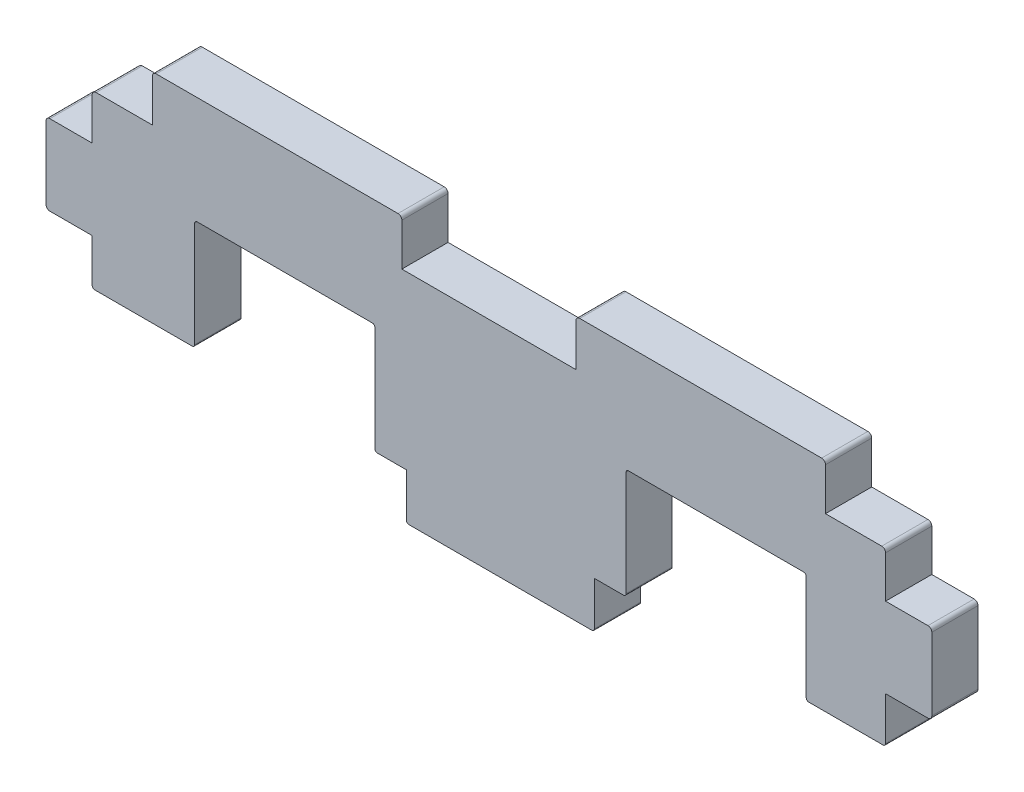
SolidWorks part; units mm, degrees
material "Acrylic (Medium-high impact)"
ref_plane "Front Plane" through (0, 0, 0) normal (0, 0, 1) x (1, 0, 0)
ref_plane "Top Plane" through (0, 0, 0) normal (0, 1, 0) x (1, 0, 0)
ref_plane "Right Plane" through (0, 0, 0) normal (1, 0, 0) x (0, 0, -1)
sketch "Sketch2" plane through (0, 0, 0) normal (0, 0, 1) x (1, 0, 0)
  line L0 (53.6522, 7.7906) -> (53.6522, 4.9881)
  line L2 (-0.8478, 8.0406) -> (-0.8478, 12.7406)
  line L3 (6.3022, 18.9593) -> (22.0022, 18.9593)
  line L4 (56.6522, 8.0406) -> (56.6522, 12.7406)
  line L5 (48.5022, 4.9881) -> (48.5022, 11.8056)
  line L6 (48.3359, 11.9718) -> (36.9684, 11.9718)
  line L7 (36.8022, 4.9881) -> (36.8022, 11.8056)
  line L8 (48.5022, 3.4718) -> (36.8022, 11.9718) construction
  line L9 (48.5022, 11.9718) -> (36.8022, 3.4718) construction
  line L10 (33.8022, 18.9593) -> (49.5022, 18.9593)
  line L11 (2.4022, 15.9593) -> (6.0522, 15.9593)
  line L12 (2.1522, 12.9906) -> (2.1522, 15.7093)
  line L14 (20.5022, 4.9881) -> (20.5022, 11.8056)
  line L15 (20.3359, 11.9718) -> (8.9684, 11.9718)
  line L16 (8.8022, 4.9881) -> (8.8022, 11.8056)
  line L17 (20.5022, 3.4718) -> (8.8022, 11.9718) construction
  line L18 (20.5022, 11.9718) -> (8.8022, 3.4718) construction
  line L19 (53.4859, 4.8218) -> (48.6684, 4.8218)
  line L20 (36.6359, 4.8218) -> (34.7522, 4.8218)
  line L21 (49.7522, 15.9593) -> (53.4022, 15.9593)
  line L22 (6.0522, 15.9593) -> (6.0522, 18.7093)
  line L23 (34.7522, 4.8218) -> (34.7522, 1.9881)
  line L24 (22.2522, 15.9593) -> (22.2522, 18.7093)
  line L25 (34.5859, 1.8218) -> (22.7184, 1.8218)
  line L26 (33.5522, 18.7093) -> (33.5522, 15.9593)
  line L27 (-0.5978, 12.9906) -> (2.1522, 12.9906)
  line L28 (49.7522, 18.7093) -> (49.7522, 15.9593)
  line L29 (22.2522, 15.9593) -> (33.5522, 15.9593)
  line L30 (22.5522, 1.9881) -> (22.5522, 4.8218)
  line L31 (-0.5978, 7.7906) -> (2.1522, 7.7906)
  line L32 (53.6522, 12.9906) -> (53.6522, 15.7093)
  line L33 (22.5522, 4.8218) -> (20.6684, 4.8218)
  line L34 (56.4022, 12.9906) -> (53.6522, 12.9906)
  line L35 (8.6359, 4.8218) -> (2.3184, 4.8218)
  line L36 (56.4022, 7.7906) -> (53.6522, 7.7906)
  line L37 (2.1522, 4.9881) -> (2.1522, 7.7906)
  arc A0 (6.3022, 18.9593) -> (6.0522, 18.7093) centre (6.3022, 18.7093) ccw
  arc A1 (22.2522, 18.7093) -> (22.0022, 18.9593) centre (22.0022, 18.7093) ccw
  arc A2 (33.8022, 18.9593) -> (33.5522, 18.7093) centre (33.8022, 18.7093) ccw
  arc A3 (49.7522, 18.7093) -> (49.5022, 18.9593) centre (49.5022, 18.7093) ccw
  arc A4 (56.6522, 12.7406) -> (56.4022, 12.9906) centre (56.4022, 12.7406) ccw
  arc A5 (56.4022, 7.7906) -> (56.6522, 8.0406) centre (56.4022, 8.0406) ccw
  arc A6 (2.3184, 4.8218) -> (2.1522, 4.9881) centre (2.3184, 4.9881) cw
  arc A7 (8.6359, 4.8218) -> (8.8022, 4.9881) centre (8.6359, 4.9881) ccw
  arc A8 (8.9684, 11.9718) -> (8.8022, 11.8056) centre (8.9684, 11.8056) ccw
  arc A9 (20.5022, 11.8056) -> (20.3359, 11.9718) centre (20.3359, 11.8056) ccw
  arc A10 (-0.8478, 8.0406) -> (-0.5978, 7.7906) centre (-0.5978, 8.0406) ccw
  arc A11 (-0.5978, 12.9906) -> (-0.8478, 12.7406) centre (-0.5978, 12.7406) ccw
  arc A12 (20.6684, 4.8218) -> (20.5022, 4.9881) centre (20.6684, 4.9881) cw
  arc A13 (53.6522, 15.7093) -> (53.4022, 15.9593) centre (53.4022, 15.7093) ccw
  arc A14 (22.7184, 1.8218) -> (22.5522, 1.9881) centre (22.7184, 1.9881) cw
  arc A15 (2.1522, 15.7093) -> (2.4022, 15.9593) centre (2.4022, 15.7093) cw
  arc A16 (34.7522, 1.9881) -> (34.5859, 1.8218) centre (34.5859, 1.9881) cw
  arc A17 (36.6359, 4.8218) -> (36.8022, 4.9881) centre (36.6359, 4.9881) ccw
  arc A18 (36.9684, 11.9718) -> (36.8022, 11.8056) centre (36.9684, 11.8056) ccw
  arc A19 (48.5022, 11.8056) -> (48.3359, 11.9718) centre (48.3359, 11.8056) ccw
  arc A20 (48.6684, 4.8218) -> (48.5022, 4.9881) centre (48.6684, 4.9881) cw
  arc A21 (53.6522, 4.9881) -> (53.4859, 4.8218) centre (53.4859, 4.9881) cw
  point P8 (42.6522, 7.7218)
  point P14 (14.6522, 7.7218)
  point P60 (2.1522, 4.8218)
  point P71 (20.5022, 4.8218)
  point P74 (22.5522, 1.8218)
  point P77 (34.7522, 1.8218)
  point P80 (36.8022, 4.8218)
  point P89 (48.5022, 4.8218)
  point P92 (53.6522, 4.8218)
  dimension "D19" = 0.5
  dimension "D24" = 0.5
  dimension "D27" = 0.5
  dimension "D30" = 0.5
  dimension "D33" = 0.5
  dimension "D44" = 3
  dimension "D45" = 2.9
  dimension "D46" = 2.9687
  dimension "D47" = 0.1662
  dimension "D48" = 0.5
  dimension "D51" = 0.5
  dimension "D54" = 0.5
  dimension "D11" = 8.5
  dimension "D15" = 8.5
  dimension "D1" = 5.2
  dimension "D4" = 3
  dimension "D6" = 11
  dimension "D7" = 39
  dimension "D8" = 11.7
  dimension "D9" = 11.7
  dimension "D10" = 2.9688
  dimension "D12" = 5.2
  dimension "D13" = 57.5
  dimension "D14" = 6.9
  dimension "D16" = 16.2
  dimension "D17" = 6.9
  dimension "D18" = 16.2
  dimension "D20" = 0.25
  dimension "D21" = 0.25
  dimension "D22" = 0.25
  dimension "D23" = 0.25
  dimension "D25" = 0.25
  dimension "D26" = 0.25
  dimension "D28" = 0.25
  dimension "D29" = 0.25
  dimension "D31" = 0.25
  dimension "D32" = 0.25
  dimension "D34" = 0.25
  dimension "D35" = 0.25
  dimension "D36" = 2.9688
  dimension "D37" = 2.9688
  dimension "D38" = 3
  dimension "D39" = 2.9
  dimension "D40" = 12.2
  dimension "D41" = 2.05
  dimension "D42" = 2.05
  dimension "D43" = 3
  dimension "D49" = 0.25
  dimension "D50" = 0.25
  dimension "D52" = 0.25
  dimension "D53" = 0.25
  dimension "D56" = 3
extrude "Boss-Extrude1" add sketch "Sketch2" along normal blind 3
